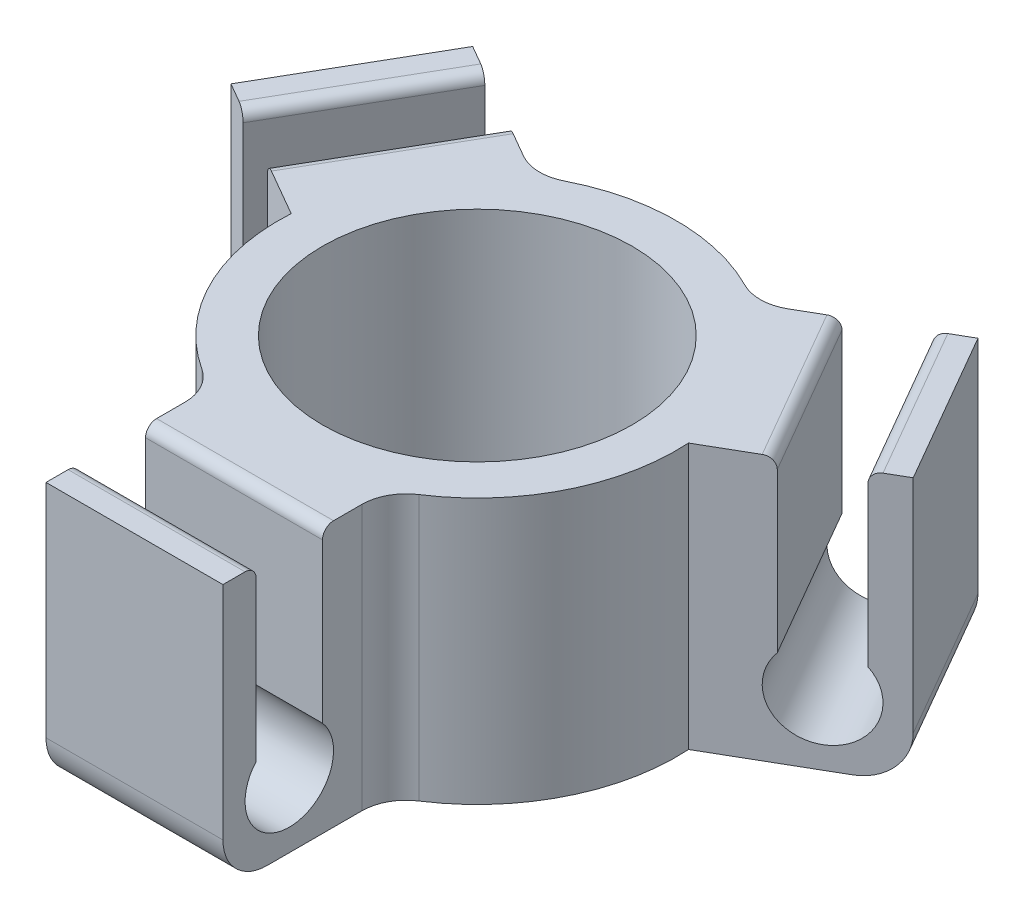
SolidWorks part; units mm, degrees
material "Rubber"
ref_plane "Front Plane" through (0, 0, 0) normal (0, 0, 1) x (1, 0, 0)
ref_plane "Top Plane" through (0, 0, 0) normal (0, 1, 0) x (1, 0, 0)
ref_plane "Right Plane" through (0, 0, 0) normal (1, 0, 0) x (0, 0, -1)
sketch "Sketch1" plane through (0, 0, 0) normal (0, 1, 0) x (1, 0, 0)
  circle A0 centre (0, 0) radius 7
  circle A1 centre (0, 0) radius 9
extrude "Boss-Extrude1" add sketch "Sketch1" along normal blind 12
ref_plane "Plane1" through (0, 0, 9) normal (0, 0, 1) x (1, 0, 0)
sketch "Sketch2" plane through (0, 0, 9) normal (0, 0, 1) x (1, 0, 0)
  line L0 (-4, 12) -> (4, 12)
  line L2 (9, 12) -> (-9, 12) construction
  line L3 (-4, 12) -> (-4, 0)
  line L4 (-9, 0) -> (9, 0) construction
  line L5 (-4, 0) -> (4, 0)
  line L6 (4, 0) -> (4, 12)
  point P3 (0, 12)
extrude "Boss-Extrude2" add sketch "Sketch2" along normal blind 0.5 and the other way up to surface
sketch "Sketch3" plane through (-4, 0, 0) normal (-1, 0, 0) x (0, 0, 1)
  line L0 (9.5, 0) -> (12.5, 0)
  line L1 (12.5, 0) -> (15.5, 0)
  line L2 (15.5, 0) -> (15.5, 12)
  line L3 (15.5, 12) -> (14, 12)
  line L4 (14, 12) -> (14, 3)
  line L5 (14, 3) -> (11, 3)
  line L6 (11, 3) -> (11, 12)
  line L7 (11, 12) -> (9.5, 12)
  line L8 (9.5, 12) -> (9.5, 0)
extrude "Boss-Extrude3" add sketch "Sketch3" against normal blind 8
sketch "Sketch4" plane through (-4, 0, 0) normal (-1, 0, 0) x (0, 0, 1)
  line L0 (14, 3) -> (11, 3) construction
  circle A0 centre (12.5, 3) radius 2
extrude "Cut-Extrude1" cut sketch "Sketch4" against normal blind 11
pattern_circular "CirPattern1" count 3 every 120 about axis through (0, 0, 0) along (0, 1, 0) of "Boss-Extrude2", "Boss-Extrude3", "Cut-Extrude1"
fillet "Fillet1" radius 2 7 edges at (-13.4234, 0, -7.75) (4, 6, 8.0623) (-4, 6, 8.0623) (0, 0, 15.5) (4.9821, 6, -7.4952) (-4.9821, 6, -7.4952) (13.4234, 0, -7.75)
fillet "Fillet2" radius 0.5 6 edges at (-12.1244, 12, -7) (0, 12, 11) (0, 12, 14) (9.5263, 12, -5.5) (12.1244, 12, -7) (-9.5263, 12, -5.5)
